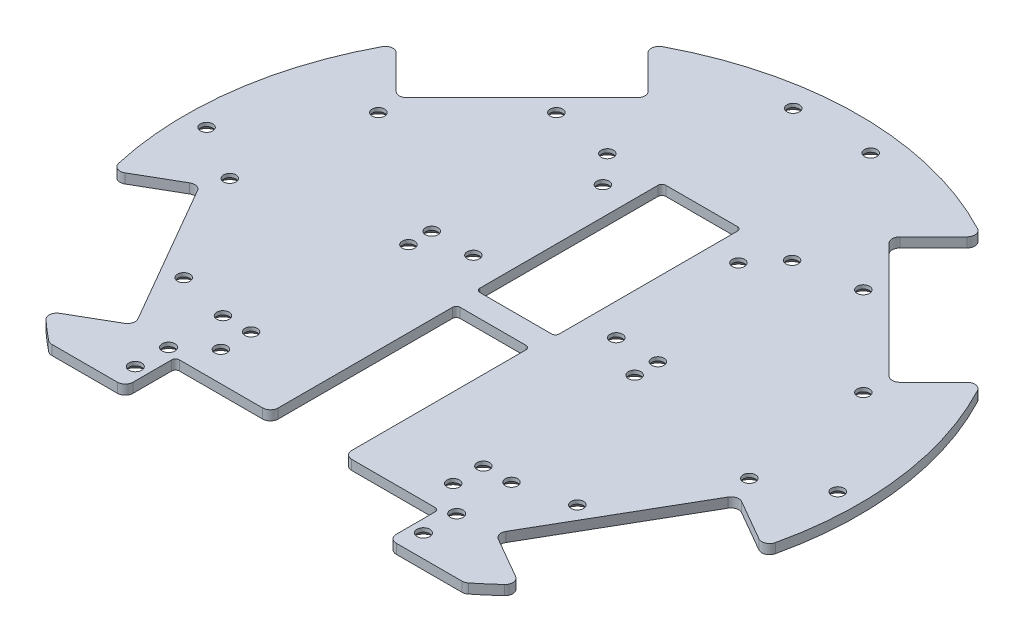
SolidWorks part; units mm, degrees
ref_plane "Plano frontal" through (0, 0, 0) normal (0, 0, 1) x (1, 0, 0)
ref_plane "Plano superior" through (0, 0, 0) normal (0, 1, 0) x (1, 0, 0)
ref_plane "Plano direito(CENTRAL)" through (0, 0, 0) normal (1, 0, 0) x (0, 0, -1)
sketch "Esboço3" plane through (0, 0, 0) normal (0, 1, 0) x (1, 0, 0)
  line L0 (0, 0) -> (0, 52.1999) construction
  line L1 (-52.941, -68.5) -> (52.941, -68.5)
  line L2 (0, 0) -> (68.1914, -88.2323) construction
  line L4 (0, 0) -> (75.3442, -43.5) construction
  line L5 (81.8562, -20.7016) -> (71.2558, -14.5814)
  line L6 (68.5237, -15.3135) -> (47.5237, -51.6865)
  line L7 (48.2558, -54.4186) -> (58.8562, -60.5388)
  line L8 (0, 0) -> (61.5183, 61.5183) construction
  line L9 (41.1822, 73.7091) -> (32.5269, 65.0538)
  line L10 (32.5269, 62.2254) -> (62.2254, 32.5269)
  line L11 (65.0538, 32.5269) -> (73.7091, 41.1822)
  line L12 (-65.0538, 32.5269) -> (-73.7091, 41.1822)
  line L13 (-32.5269, 62.2254) -> (-62.2254, 32.5269)
  line L14 (-41.1822, 73.7091) -> (-32.5269, 65.0538)
  line L15 (-48.2558, -54.4186) -> (-58.8562, -60.5388)
  line L16 (-68.5237, -15.3135) -> (-47.5237, -51.6865)
  line L17 (-81.8562, -20.7016) -> (-71.2558, -14.5814)
  line L20 (0, 0) -> (40.5982, 0) construction
  line L21 (0, 87) -> (-87, 87) construction
  line L22 (-87, 87) -> (-87, 0) construction
  arc A0 (54.1867, -68.0647) -> (-54.1867, -68.0647) centre (0, 0) ccw construction
  arc A1 (40.7037, 76.8909) -> (-40.7037, 76.8909) centre (0, 0) ccw
  arc A2 (76.8909, 40.7037) -> (84.8058, -19.4159) centre (0, 0) cw
  arc A3 (59.2176, -63.736) -> (54.1867, -68.0647) centre (0, 0) cw
  arc A4 (41.1822, 73.7091) -> (40.7037, 76.8909) centre (39.768, 75.1233) ccw
  arc A5 (73.7091, 41.1822) -> (76.8909, 40.7037) centre (75.1233, 39.768) cw
  arc A6 (81.8562, -20.7016) -> (84.8058, -19.4159) centre (82.8562, -18.9696) ccw
  arc A7 (58.8562, -60.5388) -> (59.2176, -63.736) centre (57.8562, -62.2708) cw
  arc A8 (52.941, -68.5) -> (54.1867, -68.0647) centre (52.941, -66.5) ccw
  arc A11 (47.5237, -51.6865) -> (48.2558, -54.4186) centre (49.2558, -52.6865) ccw
  arc A12 (71.2558, -14.5814) -> (68.5237, -15.3135) centre (70.2558, -16.3135) ccw
  arc A13 (32.5269, 65.0538) -> (32.5269, 62.2254) centre (33.9411, 63.6396) ccw
  arc A14 (62.2254, 32.5269) -> (65.0538, 32.5269) centre (63.6396, 33.9411) ccw
  arc A15 (-62.2254, 32.5269) -> (-65.0538, 32.5269) centre (-63.6396, 33.9411) cw
  arc A16 (-32.5269, 65.0538) -> (-32.5269, 62.2254) centre (-33.9411, 63.6396) cw
  arc A17 (-71.2558, -14.5814) -> (-68.5237, -15.3135) centre (-70.2558, -16.3135) cw
  arc A18 (-47.5237, -51.6865) -> (-48.2558, -54.4186) centre (-49.2558, -52.6865) cw
  arc A21 (-52.941, -68.5) -> (-54.1867, -68.0647) centre (-52.941, -66.5) cw
  arc A22 (-58.8562, -60.5388) -> (-59.2176, -63.736) centre (-57.8562, -62.2708) ccw
  arc A23 (-81.8562, -20.7016) -> (-84.8058, -19.4159) centre (-82.8562, -18.9696) cw
  arc A24 (-73.7091, 41.1822) -> (-76.8909, 40.7037) centre (-75.1233, 39.768) ccw
  arc A25 (-41.1822, 73.7091) -> (-40.7037, 76.8909) centre (-39.768, 75.1233) cw
  arc A26 (-59.2176, -63.736) -> (-54.1867, -68.0647) centre (0, 0) ccw
  arc A27 (-76.8909, 40.7037) -> (-84.8058, -19.4159) centre (0, 0) ccw
  point P1 (-63.6396, 31.1127)
  point P24 (43.0661, 75.593)
  point P27 (75.593, 43.0661)
  point P30 (84.1636, -22.0338)
  point P33 (61.1636, -61.8709)
  point P45 (46.5237, -53.4186)
  point P48 (69.5237, -13.5814)
  point P51 (31.1127, 63.6396)
  point P54 (63.6396, 31.1127)
  point P88 (-31.1127, 63.6396)
  point P89 (-69.5237, -13.5814)
  point P90 (-46.5237, -53.4186)
  point P93 (-61.1636, -61.8709)
  point P94 (-84.1636, -22.0338)
  point P95 (-75.593, 43.0661)
  point P96 (-43.0661, 75.593)
  dimension "D1" = 87
  dimension "D13" = 2
  dimension "D3" = 2
  dimension "D2" = 105.882
  dimension "D4" = 67
  dimension "D5" = 30
  dimension "D6" = 46
  dimension "D7" = 23
  dimension "D8" = 67
  dimension "D9" = 45
  dimension "D10" = 46
  dimension "D12" = 23
extrude "Ressalto-extrusão1" add sketch "Esboço3" along normal blind 2.5
sketch "Esboço18" plane through (0, 0, 0) normal (0, -1, 0) x (1, 0, 0)
  circle A0 centre (16.6, -38.35) radius 1.6
  circle A1 centre (23.85, -45.85) radius 1.6
  circle A2 centre (-16.6, -38.35) radius 1.6
  circle A3 centre (-23.85, -45.85) radius 1.6
sketch "Esboço10" plane through (0, 2.5, 0) normal (0, 1, 0) x (1, 0, 0)
  line L0 (-78.5, 0) -> (78.5, 0) construction
  line L1 (0, 0) -> (0, 91.1739) construction
  line L2 (-52.941, -68.5) -> (52.941, -68.5) construction
  line L3 (0, 0) -> (131.7521, -76.0671) construction
  line L4 (0, 0) -> (0, -78.752) construction
  line L5 (-29.2, 5.85) -> (-6.741, 5.85) construction
  line L6 (-17.5, 38.35) -> (17.5, 38.35) construction
  line L7 (0, 0) -> (116.4282, 116.4282) construction
  line L8 (-37.2, -62.7) -> (-37.2, -54.1) construction
  line L9 (37.2, -54.1) -> (37.2, -62.7) construction
  line L10 (-37.2, -58.4) -> (37.2, -58.4) construction
  line L12 (139.1698, -68.8027) -> (20, 0) construction
  line L13 (14.1421, 0) -> (150.8073, 136.6651) construction
  line L15 (50.8284, -36.5627) -> (67.0784, -8.4168) construction
  line L19 (39.6333, 48.4722) -> (62.6143, 25.4912) construction
  circle A2 centre (-29.2, -0.15) radius 1.6
  circle A3 centre (67.0784, -8.4168) radius 1.6
  circle A4 centre (50.8284, -36.5627) radius 1.6
  circle A5 centre (78.5, 0) radius 1.25 construction
  circle A6 centre (-29.2, 5.85) radius 1.6
  circle A7 centre (-23.85, 45.85) radius 1.6 construction
  circle A10 centre (23.85, 45.85) radius 1.6 construction
  circle A11 centre (62.6143, 25.4912) radius 1.6
  circle A12 centre (-78.5, 0) radius 1.25 construction
  circle A13 centre (39.6333, 48.4722) radius 1.6
  circle A14 centre (29.2, -0.15) radius 1.6
  circle A15 centre (29.2, 5.85) radius 1.6
  circle A18 centre (10, 80) radius 1.6
  circle A19 centre (-10, 80) radius 1.6
  circle A20 centre (-50.8284, -36.5627) radius 1.6
  circle A21 centre (-67.0784, -8.4168) radius 1.6
  circle A22 centre (-62.6143, 25.4912) radius 1.6
  circle A23 centre (-39.6333, 48.4722) radius 1.6
  circle A24 centre (-23.85, 45.85) radius 1.6
  circle A25 centre (-17.5, 38.35) radius 1.6
  circle A26 centre (-18.45, 5.85) radius 1.6
  circle A27 centre (18.45, 5.85) radius 1.6
  circle A28 centre (17.5, 38.35) radius 1.6
  circle A29 centre (23.85, 45.85) radius 1.6
  circle A39 centre (78.5, 0) radius 1.25 construction
  circle A46 centre (-78.5, 0) radius 1.25 construction
  circle A79 centre (37.2, -54.1) radius 1.65
  circle A80 centre (37.2, -62.7) radius 1.65
  circle A93 centre (-37.2, -62.7) radius 1.65
  circle A94 centre (-37.2, -54.1) radius 1.65
  point P20 (58.9534, -22.4897)
  point P24 (0, 38.35)
  point P35 (0, -58.4)
  dimension "D3" = 3.3
  dimension "D6" = 7.5
  dimension "D7" = 7.5
  dimension "D8" = 35
  dimension "D9" = 10
  dimension "D10" = 10
  dimension "D11" = 58.4
  dimension "D12" = 68.35
  dimension "D13" = 62.3
  dimension "D14" = 3.2
  dimension "D17" = 32.5
  dimension "D18" = 8.6
  dimension "D19" = 5.8
  dimension "D20" = 74.4
  dimension "D21" = 36.9
  dimension "D24" = 3.2
  dimension "D25" = 80
  dimension "D27" = 3.2
  dimension "D28" = 10
  dimension "D16" = 62.3
  dimension "D23" = 3.2
  dimension "D4" = 30
  dimension "D5" = 45
  dimension "D15" = 32.5
  dimension "D26" = 6
extrude "Corte-extrusão4" cut sketch "Esboço10" against normal up to next
sketch "Esboço11" plane through (0, 0, 0) normal (0, -1, 0) x (1, 0, 0)
  line L0 (-81.5, 0) -> (81.5, 0) construction
  circle A0 centre (-81.5, 0) radius 1.5
  circle A1 centre (81.5, 0) radius 1.5
  dimension "D1" = 3
  dimension "D4" = 3
  dimension "D2" = 81.5
  dimension "D3" = 81.5
extrude "Corte-extrusão7" cut sketch "Esboço11" against normal through all
sketch "Esboço15" plane through (0, 2.5, 0) normal (0, 1, 0) x (1, 0, 0)
  line L0 (30, -40) -> (30, -47.8) construction
  line L1 (30, -40) -> (37.25, -40) construction
  line L2 (0, 0) -> (0, -133.0122) construction
  circle A0 centre (37.25, -40) radius 1.6
  circle A1 centre (30, -47.8) radius 1.6
  circle A2 centre (30, -40) radius 1.6
  circle A3 centre (-30, -47.8) radius 1.6
  circle A4 centre (-37.25, -40) radius 1.6
  circle A5 centre (-30, -40) radius 1.6
  dimension "D1" = 30
  dimension "D5" = 3.2
  dimension "D2" = 40
  dimension "D3" = 7.25
  dimension "D4" = 7.8
extrude "Corte-extrusão10" cut sketch "Esboço15" against normal up to next
hole_wizard "Escareado para parafuso de máquina com cabeça chata de M31" positions "Esboço16" profile "Esboço17" countersink size "M3" standard "Ansi Metric"
sketch "Esboço16" plane through (0, 0, 0) normal (0, -1, 0) x (-1, 0, 0)
  point P0 (37.2, -62.7)
  point P3 (37.2, -54.1)
  point P6 (50.8284, -36.5627)
  point P9 (67.0784, -8.4168)
  point P12 (81.5, 0)
  point P15 (29.2, -0.15)
  point P18 (29.2, 5.85)
  point P21 (62.6143, 25.4912)
  point P24 (39.6333, 48.4722)
  point P33 (10, 80)
  point P36 (-10, 80)
  point P45 (-39.6333, 48.4722)
  point P48 (-62.6143, 25.4912)
  point P51 (-29.2, 5.85)
  point P54 (-29.2, -0.15)
  point P57 (-67.0784, -8.4168)
  point P60 (-81.5, 0)
  point P63 (-50.8284, -36.5627)
  point P66 (-37.25, -40)
  point P69 (-30, -40)
  point P72 (-30, -47.8)
  point P75 (-37.2, -54.1)
  point P78 (-37.2, -62.7)
  point P82 (30, -40)
  point P85 (30, -47.8)
  point P88 (37.25, -40)
  point P91 (18.45, 5.85)
  point P94 (-18.45, 5.85)
  point P106 (23.85, 45.85)
  point P112 (-23.85, 45.85)
  point P119 (-17.5, 38.35)
  point P122 (17.5, 38.35)
sketch "Esboço17" plane through (-37.2, 0, 62.7) normal (1, 0, 0) x (0, 0, -1)
  line L0 (0, 0) -> (0, 3.4604)
  line L1 (0, 3.4604) -> (1.6, 2.499)
  line L2 (1.6, 2.499) -> (1.6, 1.55)
  line L3 (1.6, 1.55) -> (3.15, 0)
  line L5 (3.15, 0) -> (0, 0)
  line L6 (-1.6, 1.55) -> (-3.15, 0) construction
  line L10 (0, 3.4604) -> (-1.6, 2.499) construction
  line L11 (0, -6.35) -> (0, 107.95) construction
  dimension "Hole Dia." = 3.2
  dimension "Hole Depth" = 2.499
  dimension "Near C'Sink Dia." = 6.3
  dimension "Near C'Sink Angle" = 90
  dimension "Drill Angle" = 118
sketch "Sketch1" plane through (0, 2.5, 0) normal (0, 1, 0) x (1, 0, 0)
  line L0 (0, -90.6724) -> (-25.4416, -36.1127)
  line L1 (0, -90.6724) -> (25.4416, -36.1127)
  line L2 (0, -90.6724) -> (0, -30.4724) construction
  line L3 (-22.704, 16.1413) -> (-21.6228, 11.0549)
  line L4 (-65.7182, -3.4614) -> (-62.5888, -7.6144)
  arc A0 (25.4416, -36.1127) -> (-25.4416, -36.1127) centre (0, -90.6724) ccw
  arc A1 (23.244, -40.8255) -> (-23.244, -40.8255) centre (0, -90.6724) ccw
  circle A2 centre (0, -90.6724) radius 104
  circle A3 centre (0, -90.6724) radius 109.2
  point P0 (0, -90.6724)
  dimension "D2" = 110
  dimension "D3" = 5.2
  dimension "D6" = 208
  dimension "D7" = 5.2
  dimension "D4" = 25
  dimension "D5" = 25
  dimension "D8" = 25
  dimension "D9" = 12
extrude "Cut-Extrude1" [suppressed] cut sketch "Sketch1" against normal up to next contours A1 L2 A0 L0 | L2 A1 L1 A0 | L3 A3 L4 A2
sketch "Esboço12" plane through (0, 2.5, 0) normal (0, 1, 0) x (1, 0, 0)
  line L0 (60.6989, 7.9912) -> (63.6396, 31.9411) construction
  line L1 (60.6989, 7.9912) -> (69.7381, -14.3816) construction
  arc A0 (71.2558, -14.5814) -> (68.5237, -15.3135) centre (70.2558, -16.3135) ccw construction
  arc A1 (62.2254, 32.5269) -> (65.0538, 32.5269) centre (63.6396, 33.9411) ccw construction
  circle A2 centre (60.6989, 7.9912) radius 18.5
  dimension "D1" = 37
  dimension "D2" = 151
sketch "Esboço13" plane through (0, 0, 0) normal (0, -1, 0) x (1, 0, 0)
  line L0 (0, 68.5) -> (0, 0) construction
  line L1 (-52.941, 68.5) -> (52.941, 68.5) construction
  line L3 (-8.5, 68.5) -> (8.5, 68.5)
  line L4 (-9.5, 67.5) -> (-9.5, 8.5)
  line L5 (-8.5, 7.5) -> (8.5, 7.5)
  line L6 (9.5, 67.5) -> (9.5, 8.5)
  line L7 (-9.5, 68.5) -> (9.5, 7.5) construction
  line L8 (-9.5, 7.5) -> (9.5, 68.5) construction
  line L9 (-34, 68.5) -> (34, 68.5)
  line L10 (-34, 68.5) -> (-34, 55.5)
  line L11 (-34, 55.5) -> (34, 55.5)
  line L12 (34, 68.5) -> (34, 55.5)
  line L13 (-10.25, -46.35) -> (10.25, -46.35)
  line L14 (-10.25, -46.35) -> (-10.25, 1.65)
  line L15 (-10.25, 1.65) -> (10.25, 1.65)
  line L16 (10.25, -46.35) -> (10.25, 1.65)
  arc A0 (-9.5, 8.5) -> (-8.5, 7.5) centre (-8.5, 8.5) ccw
  arc A1 (8.5, 7.5) -> (9.5, 8.5) centre (8.5, 8.5) ccw
  arc A2 (9.5, 67.5) -> (8.5, 68.5) centre (8.5, 67.5) ccw
  arc A3 (-8.5, 68.5) -> (-9.5, 67.5) centre (-8.5, 67.5) ccw
  point P5 (0, 38)
  point P22 (0, 55.5)
  point P32 (0, -46.35)
  dimension "D4" = 1
  dimension "D1" = 7.5
  dimension "D2" = 68
  dimension "D3" = 19
  dimension "D5" = 13
  dimension "D6" = 48
  dimension "D7" = 20.5
  dimension "D8" = 1.65
extrude "Corte-extrusão8" cut sketch "Esboço13" against normal through all contours A3 L9 L10 L11 L4 | A2 L6 L11 L12 L9 | L3 A3 L4 L11 L6 A2 | L5 A1 L6 L11 L4 A0 | L14 L13 L16 L15
sketch "Esboço14" plane through (0, 0, 7.5) normal (0, 0, 1) x (1, 0, 0)
  circle A0 centre (0, 15.8) radius 14.2 construction
  circle A1 centre (0, 15.8) radius 14.4
  dimension "D1" = 0.2
fillet "Filete1" radius 2 4 edges at (-34, 1.25, 68.5) (34, 1.25, 68.5) (9.5, 1.25, 55.5) (-9.5, 1.25, 55.5)
fillet "Filete2" radius 1 6 edges at (10.25, 1.25, 1.65) (-10.25, 1.25, 1.65) (-10.25, 1.25, -46.35) (10.25, 1.25, -46.35) (34, 1.25, 55.5) (-34, 1.25, 55.5)
